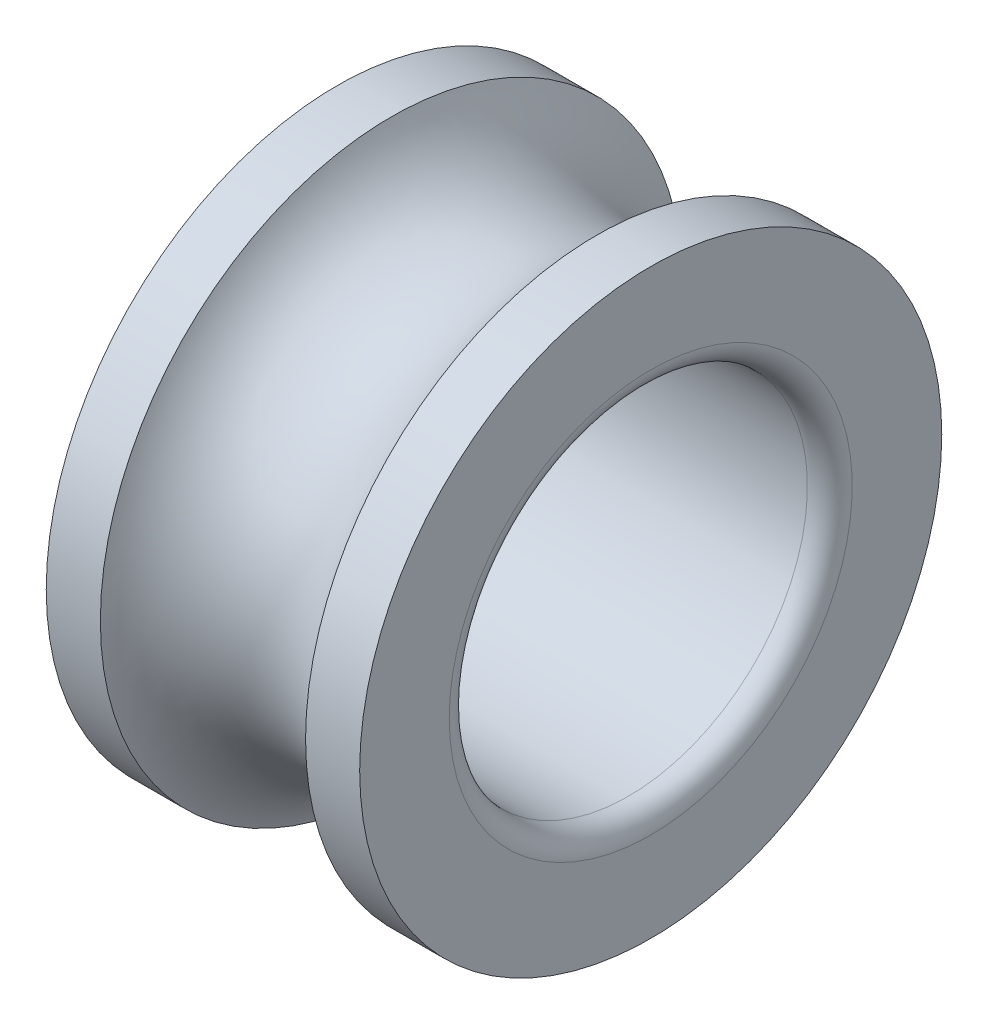
SolidWorks part; units mm, degrees
ref_plane "Plan de face" through (0, 0, 0) normal (0, 0, 1) x (1, 0, 0)
ref_plane "Plan de dessus" through (0, 0, 0) normal (0, 1, 0) x (1, 0, 0)
ref_plane "Plan de droite" through (0, 0, 0) normal (1, 0, 0) x (0, 0, -1)
sketch "Esquisse1" plane through (0, 0, 0) normal (0, 0, 1) x (1, 0, 0)
  line L0 (0, 0) -> (7, 0) construction
  line L1 (-0.1306, 7.5) -> (28.0528, 7.5) construction
  line L2 (15.6319, 29.22) -> (15.6319, -6.3402) construction
  line L3 (17.9232, 6.5) -> (19.1319, 6.5)
  line L4 (12.1319, 6.5) -> (13.3406, 6.5)
  line L5 (12.1319, 6.5) -> (12.1319, 4.5)
  line L6 (12.6319, 4) -> (18.6319, 4)
  line L7 (19.1319, 6.5) -> (19.1319, 4.5)
  arc A0 (13.3406, 6.5) -> (17.9232, 6.5) centre (15.6319, 7.5) ccw
  arc A1 (12.6319, 4) -> (12.1319, 4.5) centre (12.6319, 4.5) cw
  arc A2 (19.1319, 4.5) -> (18.6319, 4) centre (18.6319, 4.5) cw
  point P16 (12.1319, 4)
  point P19 (19.1319, 4)
  dimension "D1" = 5
  dimension "D7" = 0.5
  dimension "D2" = 3.5
  dimension "D3" = 7
  dimension "D4" = 2.5
  dimension "D5" = 3.5
  dimension "D6" = 4
revolve "Révolution1" add sketch "Esquisse1" angle 360 about L0
